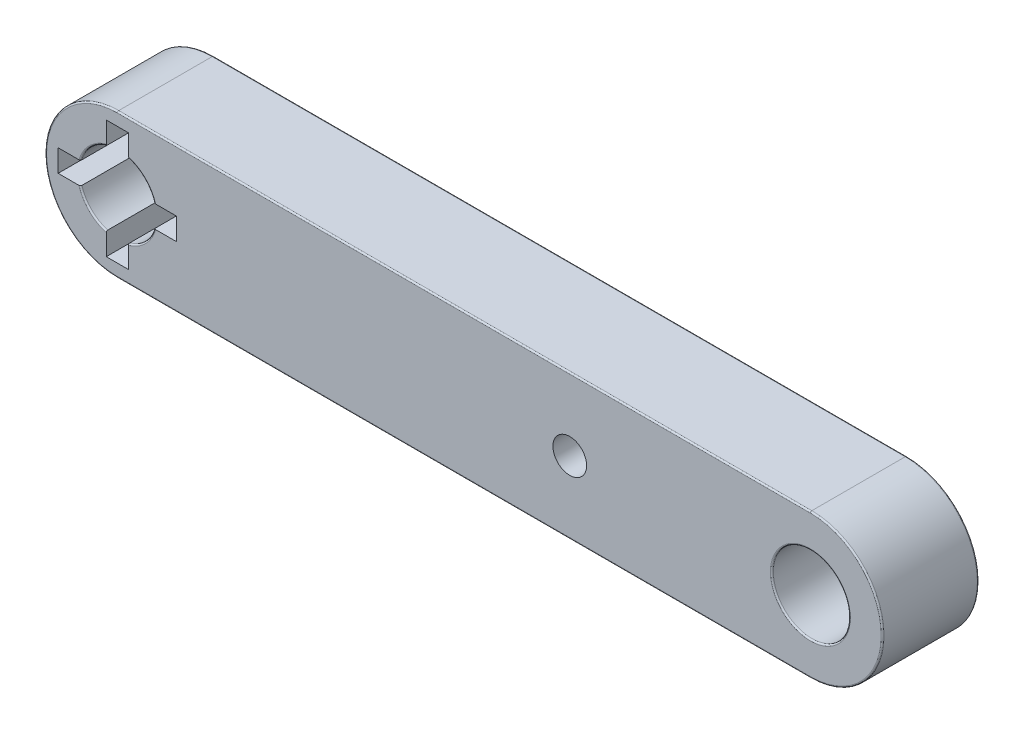
SolidWorks part; units mm, degrees
ref_plane "Front Plane" through (0, 0, 0) normal (0, 0, 1) x (1, 0, 0)
ref_plane "Top Plane" through (0, 0, 0) normal (0, 1, 0) x (1, 0, 0)
ref_plane "Right Plane" through (0, 0, 0) normal (1, 0, 0) x (0, 0, -1)
sketch "Sketch1" plane through (0, 0, 0) normal (0, 0, 1) x (1, 0, 0)
  line L1 (-36, 7.5) -> (36, 7.5) construction
  line L2 (-36, 7.5) -> (-36, -7.5) construction
  line L3 (-36, -7.5) -> (36, -7.5) construction
  line L4 (36, 7.5) -> (36, -7.5) construction
  line L5 (-36, 7.5) -> (36, -7.5) construction
  line L6 (-36, -7.5) -> (36, 7.5) construction
  line L7 (-36, 7.5) -> (36, 7.5)
  line L9 (-36, -7.5) -> (36, -7.5)
  line L11 (-36, 7.5) -> (36, -7.5) construction
  line L12 (-36, -7.5) -> (36, 7.5) construction
  arc A0 (-36, 7.5) -> (-36, -7.5) centre (-36, 0) ccw
  arc A1 (36, -7.5) -> (36, 7.5) centre (36, 0) ccw
  circle A2 centre (-36, 0) radius 4
  circle A3 centre (36, 0) radius 4
  point P0 (0, 0)
  point P12 (0, 0)
  dimension "D3" = 8
  dimension "D1" = 72
  dimension "D2" = 15
  dimension "D4" = 15
extrude "Boss-Extrude1" add sketch "Sketch1" along normal mid plane 10
fillet "Fillet2" radius 0.15 12 edges at (40, 0, -5) (-32, 0, -5) (0, 7.5, -5) (-43.5, 0, -5) (0, -7.5, -5) (43.5, 0, -5) (40, 0, 5) (-43.5, 0, 5) (0, 7.5, 5) (43.5, 0, 5) (0, -7.5, 5) (-32, 0, 5)
sketch "Sketch2" plane through (0, 0, -5) normal (0, 0, -1) x (-1, 0, 0)
  line L0 (-36, 7.5) -> (36, 7.5) construction
  line L1 (-16, 4) -> (-6, 4)
  line L2 (-16, 4) -> (-16, -3.9994)
  line L3 (-16, -3.9994) -> (-6, -3.9994)
  line L4 (-6, 4) -> (-6, -3.9994)
  line L5 (36, -7.5) -> (-36, -7.5) construction
  circle A0 centre (-36, 0) radius 4.15 construction
  dimension "D3" = 20
  dimension "D1" = 3.5
  dimension "D2" = 3.5006
  dimension "D4" = 30
extrude "Cut-Extrude1" cut sketch "Sketch2" against normal blind 3
sketch "Sketch3" plane through (0, 0, -2) normal (0, 0, -1) x (-1, 0, 0)
  line L0 (-16, 4) -> (-6, -3.9994) construction
  line L1 (-16, -3.9994) -> (-6, 4) construction
  circle A0 centre (-11, 0.0003) radius 1.75
  dimension "D1" = 3.5
extrude "Cut-Extrude2" cut sketch "Sketch3" against normal through all
sketch "Sketch4" plane through (0, 0, 5) normal (0, 0, 1) x (1, 0, 0)
  line L24 (-29.85, 1.15) -> (-32.1689, 1.15)
  line L25 (-34.85, 3.8311) -> (-34.85, 6.15)
  line L26 (-34.85, 6.15) -> (-37.15, 6.15)
  line L27 (-37.15, 6.15) -> (-37.15, 3.8311)
  line L28 (-39.8311, 1.15) -> (-42.15, 1.15)
  line L29 (-42.15, 1.15) -> (-42.15, -1.15)
  line L30 (-42.15, -1.15) -> (-39.8311, -1.15)
  line L31 (-37.15, -3.8311) -> (-37.15, -6.15)
  line L32 (-37.15, -6.15) -> (-34.85, -6.15)
  line L33 (-34.85, -6.15) -> (-34.85, -3.8311)
  line L34 (-32.1689, -1.15) -> (-29.85, -1.15)
  line L35 (-29.85, -1.15) -> (-29.85, 1.15)
  line L36 (-29.85, 1.15) -> (-32.1689, 1.15)
  line L37 (-34.85, 3.8311) -> (-34.85, 6.15)
  line L38 (-34.85, 6.15) -> (-37.15, 6.15)
  line L39 (-37.15, 6.15) -> (-37.15, 3.8311)
  line L40 (-39.8311, 1.15) -> (-42.15, 1.15)
  line L41 (-42.15, 1.15) -> (-42.15, -1.15)
  line L42 (-42.15, -1.15) -> (-39.8311, -1.15)
  line L43 (-37.15, -3.8311) -> (-37.15, -6.15)
  line L44 (-37.15, -6.15) -> (-34.85, -6.15)
  line L45 (-34.85, -6.15) -> (-34.85, -3.8311)
  line L46 (-32.1689, -1.15) -> (-29.85, -1.15)
  line L47 (-29.85, -1.15) -> (-29.85, 1.15)
  arc A8 (-32.1689, 1.15) -> (-34.85, 3.8311) centre (-36, 0) ccw
  arc A9 (-37.15, 3.8311) -> (-39.8311, 1.15) centre (-36, 0) ccw
  arc A10 (-39.8311, -1.15) -> (-37.15, -3.8311) centre (-36, 0) ccw
  arc A11 (-34.85, -3.8311) -> (-32.1689, -1.15) centre (-36, 0) ccw
  arc A12 (-32.1689, 1.15) -> (-34.85, 3.8311) centre (-36, 0) ccw
  arc A13 (-37.15, 3.8311) -> (-39.8311, 1.15) centre (-36, 0) ccw
  arc A14 (-39.8311, -1.15) -> (-37.15, -3.8311) centre (-36, 0) ccw
  arc A15 (-34.85, -3.8311) -> (-32.1689, -1.15) centre (-36, 0) ccw
  dimension "D1" = 0.15
extrude "Cut-Extrude3" cut sketch "Sketch4" against normal through all
